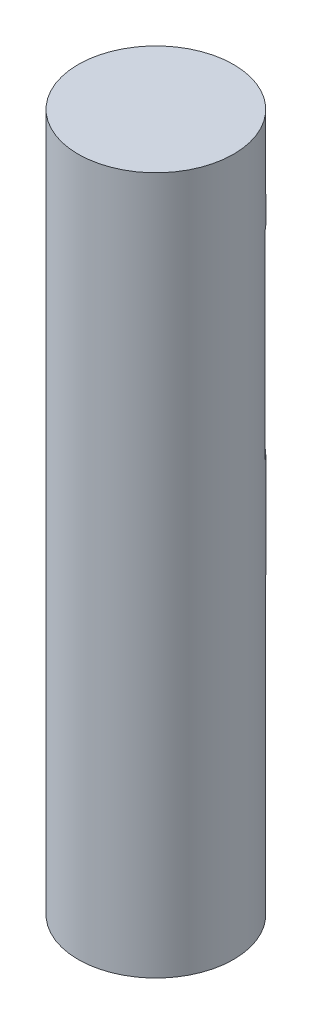
SolidWorks part; units mm, degrees
ref_plane "Front Plane" through (0, 0, 0) normal (0, 0, 1) x (1, 0, 0)
ref_plane "Top Plane" through (0, 0, 0) normal (0, 1, 0) x (1, 0, 0)
ref_plane "Right Plane" through (0, 0, 0) normal (1, 0, 0) x (0, 0, -1)
sketch "Sketch1" plane through (0, 0, 0) normal (0, 1, 0) x (1, 0, 0)
  line L0 (-3.9411, 3) -> (3.9411, 3)
  arc A0 (-3.9411, 3) -> (3.9411, 3) centre (0, 0) ccw
  dimension "D1" = 9.906
  dimension "D2" = 3
extrude "Boss-Extrude1" add sketch "Sketch1" along normal blind 44.45
sketch "Sketch3" plane through (0, 0, 0) normal (0, -1, 0) x (1, 0, 0)
  line L0 (-3.9411, -3) -> (3.9411, -3)
  arc A0 (-3.9411, -3) -> (3.9411, -3) centre (0, 0) ccw
extrude "Boss-Extrude2" add sketch "Sketch3" against normal blind 25.4
sketch "Sketch4" plane through (0, 44.45, 0) normal (0, 1, 0) x (1, 0, 0)
  line L0 (-3.9411, 3) -> (3.9411, 3)
  arc A0 (-3.9411, 3) -> (3.9411, 3) centre (0, 0) cw
  arc A1 (-3.9411, 3) -> (3.9411, 3) centre (0, 0) ccw construction
extrude "Boss-Extrude3" add sketch "Sketch4" against normal blind 6.35
